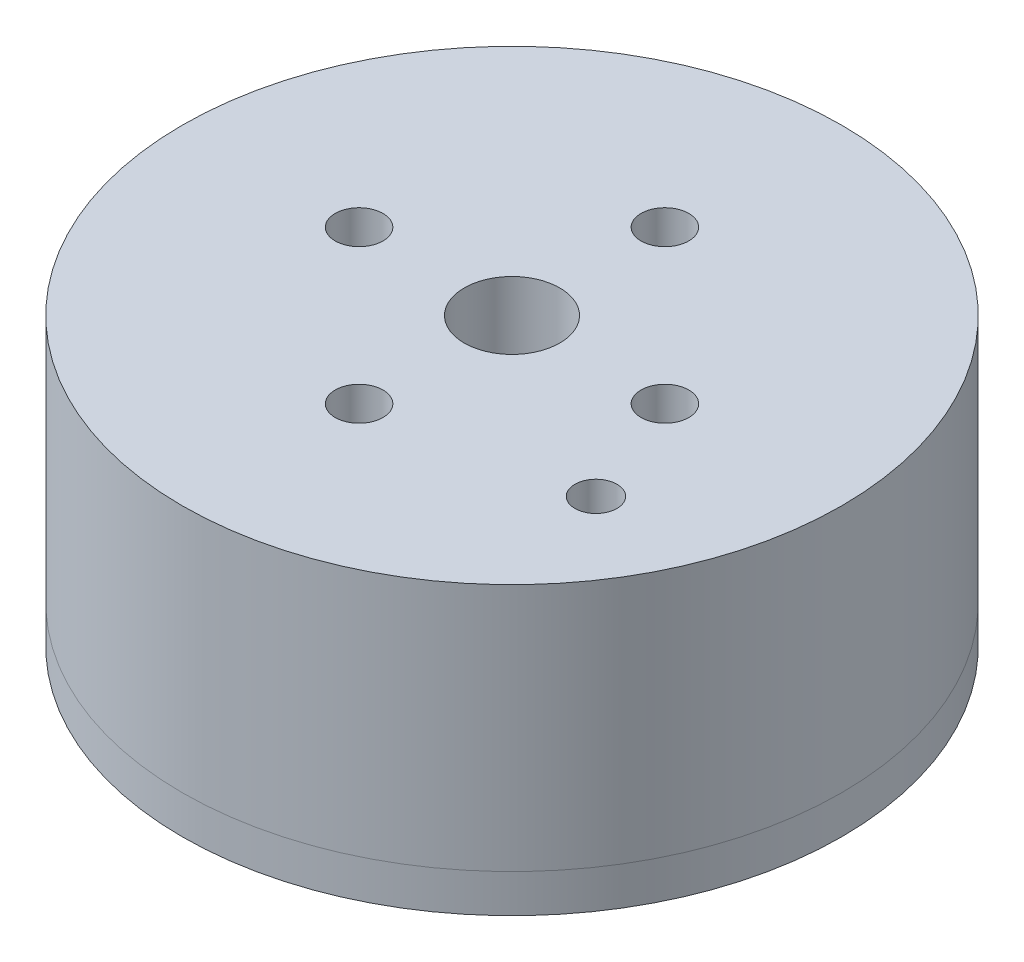
SolidWorks part; units mm, degrees
ref_plane "前视基准面" through (0, 0, 0) normal (0, 0, 1) x (1, 0, 0)
ref_plane "上视基准面" through (0, 0, 0) normal (0, 1, 0) x (1, 0, 0)
ref_plane "右视基准面" through (0, 0, 0) normal (1, 0, 0) x (0, 0, -1)
sketch "草图1" plane through (0, 0, 0) normal (0, 1, 0) x (1, 0, 0)
  line L0 (0, 0) -> (15.3077, 0) construction
  line L1 (0, 0) -> (0, 11.2653) construction
  line L2 (10.3923, -6) -> (0, 0) construction
  circle A0 centre (0, 0) radius 17.25
  circle A1 centre (0, 0) radius 2.5
  circle A2 centre (8, 0) radius 1.25
  circle A3 centre (0, -8) radius 1.25
  circle A4 centre (-8, 0) radius 1.25
  circle A5 centre (0, 8) radius 1.25
  circle A6 centre (10.3923, -6) radius 1.1
  dimension "D1" = 34.5
  dimension "D2" = 5
  dimension "D3" = 2.5
  dimension "D6" = 2.2
  dimension "D5" = 16
  dimension "D7" = 12
  dimension "D8" = 30
  dimension "D4" = 4
extrude "凸台-拉伸1" add sketch "草图1" against normal blind 13
sketch "草图2" plane through (0, -13, 0) normal (0, -1, 0) x (1, 0, 0)
  line L0 (0, 0) -> (14.3909, 0) construction
  line L1 (0, 0) -> (0, 5.8114) construction
  line L2 (0, 0) -> (6.7, 6.7) construction
  circle A0 centre (0, 0) radius 17.25
  circle A1 centre (0, 0) radius 17.25 construction
  circle A2 centre (6.7, 6.7) radius 1.25
  circle A3 centre (6.7, -6.7) radius 1.25
  circle A4 centre (-6.7, -6.7) radius 1.25
  circle A5 centre (-6.7, 6.7) radius 1.25
  circle A6 centre (0, 0) radius 4.5
  dimension "D1" = 2.5
  dimension "D5" = 9
  dimension "D3" = 13.4
  dimension "D4" = 45
  dimension "D2" = 4
extrude "凸台-拉伸3" add sketch "草图2" along normal blind 2 separate body
sketch "草图3" plane through (0, -13, 0) normal (0, -1, 0) x (1, 0, 0)
  circle A0 centre (0, 0) radius 2.5 construction
  circle A1 centre (0, 0) radius 2.5
extrude "拉伸-薄壁1" add sketch "草图3" along normal up to surface (2 mm away) thin up to face at (-6.7, -15, -7.95) thin type mid plane wall 0.3
